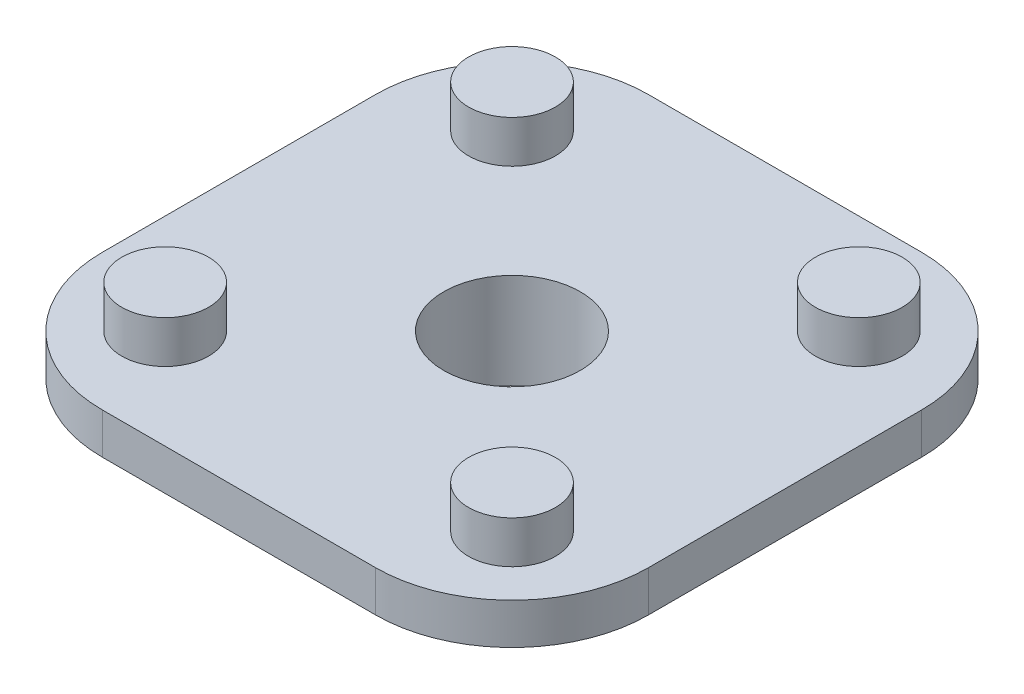
SolidWorks part; units mm, degrees
ref_plane "前视基准面" through (0, 0, 0) normal (0, 0, 1) x (1, 0, 0)
ref_plane "上视基准面" through (0, 0, 0) normal (0, 1, 0) x (1, 0, 0)
ref_plane "右视基准面" through (0, 0, 0) normal (1, 0, 0) x (0, 0, -1)
other "Configuration Table"
sketch "草图1" plane through (0, 0, 0) normal (0, 1, 0) x (1, 0, 0)
  line L1 (-10, 20) -> (10, 20)
  line L2 (-20, 10) -> (-20, -10)
  line L3 (-10, -20) -> (10, -20)
  line L4 (20, 10) -> (20, -10)
  line L5 (-20, 20) -> (20, -20) construction
  line L6 (-20, -20) -> (20, 20) construction
  arc A0 (-20, -10) -> (-10, -20) centre (-10, -10) ccw
  arc A1 (10, -20) -> (20, -10) centre (10, -10) ccw
  arc A2 (10, 20) -> (20, 10) centre (10, 10) cw
  arc A3 (-10, 20) -> (-20, 10) centre (-10, 10) ccw
  point P0 (0, 0)
  dimension "D3" = 10
  dimension "D1" = 40
  dimension "D2" = 40
extrude "凸台-拉伸1" add sketch "草图1" along normal blind 3
sketch "草图2" plane through (0, 3, 0) normal (0, 1, 0) x (1, 0, 0)
  line L0 (0, 0) -> (0, 17.6848) construction
  line L1 (0, 0) -> (16.6485, 0) construction
  circle A0 centre (12.7, 12.7) radius 3.18
  circle A1 centre (12.7, -12.7) radius 3.18
  circle A2 centre (-12.7, -12.7) radius 3.18
  circle A3 centre (-12.7, 12.7) radius 3.18
  dimension "D1" = 12.7
  dimension "D2" = 12.7
extrude "凸台-拉伸2" add sketch "草图2" along normal blind 3.1
sketch "草图3" plane through (0, 3, 0) normal (0, 1, 0) x (1, 0, 0)
  circle A0 centre (0, 0) radius 5
extrude "切除-拉伸1" cut sketch "草图3" against normal blind 3.1
sketch "草图4" plane through (0, 0, 0) normal (0, -1, 0) x (1, 0, 0)
  circle A0 centre (0, 0) radius 7.5
  circle A4 centre (0, 0) radius 5
  circle A5 centre (0, 0) radius 5
  point P3 (0, 0)
  dimension "D1" = 0
extrude "凸台-拉伸3" add sketch "草图4" along normal blind 4
